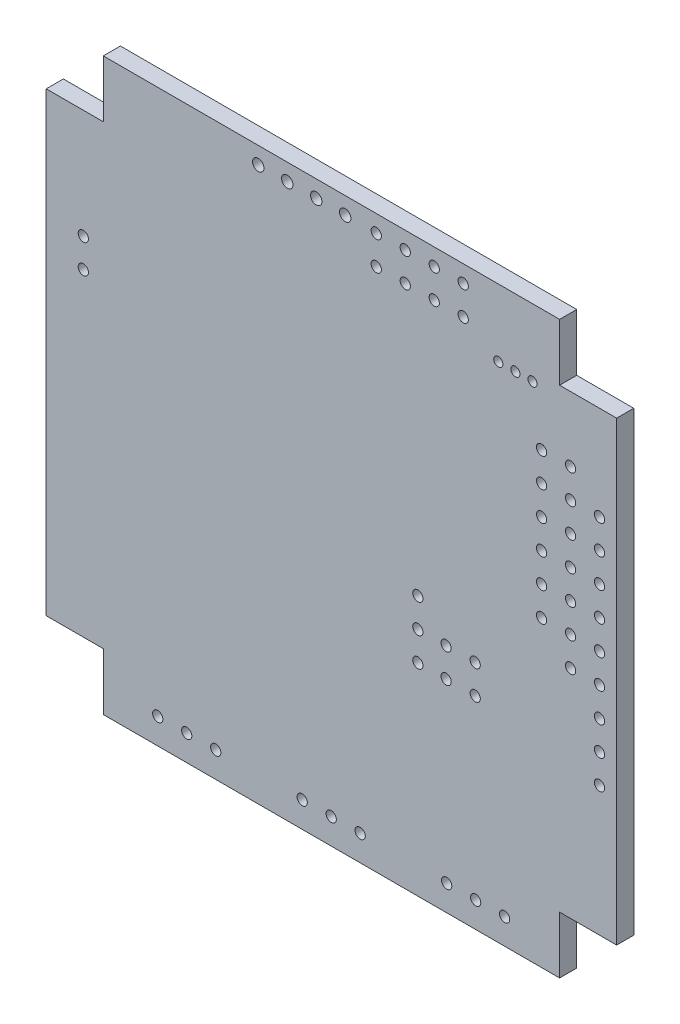
SolidWorks part; units mm, degrees
ref_plane "Спереди" through (0, 0, 0) normal (0, 0, 1) x (1, 0, 0)
ref_plane "Сверху" through (0, 0, 0) normal (0, 1, 0) x (1, 0, 0)
ref_plane "Справа" through (0, 0, 0) normal (1, 0, 0) x (0, 0, -1)
sketch "Эскиз3" plane through (0, 0, 0) normal (0, 0, 1) x (1, 0, 0)
  line L12 (24.0812, -17.7588) -> (24.0812, 22.2412)
  line L13 (19.0812, -17.7588) -> (24.0812, -17.7588)
  line L14 (19.0812, -22.7588) -> (19.0812, -17.7588)
  line L15 (-20.9188, -22.7588) -> (19.0812, -22.7588)
  line L16 (-20.9188, -17.7588) -> (-20.9188, -22.7588)
  line L17 (-25.9188, -17.7588) -> (-20.9188, -17.7588)
  line L18 (-25.9188, 22.2412) -> (-25.9188, -17.7588)
  line L19 (-20.9188, 22.2412) -> (-25.9188, 22.2412)
  line L20 (-20.9188, 27.2412) -> (-20.9188, 22.2412)
  line L21 (19.0812, 27.2412) -> (-20.9188, 27.2412)
  line L22 (19.0812, 22.2412) -> (19.0812, 27.2412)
  line L23 (24.0812, 22.2412) -> (19.0812, 22.2412)
  line L24 (24.0812, -17.7588) -> (24.0812, 22.2412)
  line L25 (19.0812, -17.7588) -> (24.0812, -17.7588)
  line L26 (19.0812, -22.7588) -> (19.0812, -17.7588)
  line L27 (-20.9188, -22.7588) -> (19.0812, -22.7588)
  line L28 (-20.9188, -17.7588) -> (-20.9188, -22.7588)
  line L29 (-25.9188, -17.7588) -> (-20.9188, -17.7588)
  line L30 (-25.9188, 22.2412) -> (-25.9188, -17.7588)
  line L31 (-20.9188, 22.2412) -> (-25.9188, 22.2412)
  line L32 (-20.9188, 27.2412) -> (-20.9188, 22.2412)
  line L33 (19.0812, 27.2412) -> (-20.9188, 27.2412)
  line L34 (19.0812, 22.2412) -> (19.0812, 27.2412)
  line L35 (24.0812, 22.2412) -> (19.0812, 22.2412)
  circle A1 centre (22.5813, 1.2412) radius 0.45
  circle A2 centre (22.5813, 1.2412) radius 0.45
  circle A3 centre (22.5813, 3.7912) radius 0.45
  circle A4 centre (22.5813, 3.7912) radius 0.45
  circle A5 centre (22.5813, 6.3412) radius 0.45
  circle A6 centre (22.5813, 6.3412) radius 0.45
  circle A7 centre (22.5813, 8.8912) radius 0.45
  circle A8 centre (22.5813, 8.8912) radius 0.45
  circle A9 centre (22.5813, 11.4412) radius 0.45
  circle A10 centre (22.5813, 11.4412) radius 0.45
  circle A11 centre (22.5813, 13.9912) radius 0.45
  circle A12 centre (22.5813, 13.9912) radius 0.45
  circle A13 centre (17.5013, 3.7912) radius 0.45
  circle A14 centre (17.5013, 3.7912) radius 0.45
  circle A15 centre (17.5013, 6.3412) radius 0.45
  circle A16 centre (17.5013, 6.3412) radius 0.45
  circle A17 centre (17.5013, 8.8912) radius 0.45
  circle A18 centre (17.5013, 8.8912) radius 0.45
  circle A19 centre (17.5013, 11.4412) radius 0.45
  circle A20 centre (17.5013, 11.4412) radius 0.45
  circle A21 centre (17.5013, 13.9912) radius 0.45
  circle A22 centre (17.5013, 13.9912) radius 0.45
  circle A23 centre (17.5013, 16.5412) radius 0.45
  circle A24 centre (17.5013, 16.5412) radius 0.45
  circle A25 centre (20.0413, 16.5412) radius 0.45
  circle A26 centre (20.0413, 16.5412) radius 0.45
  circle A27 centre (20.0413, 13.9912) radius 0.45
  circle A28 centre (20.0413, 13.9912) radius 0.45
  circle A29 centre (20.0413, 11.4412) radius 0.45
  circle A30 centre (20.0413, 11.4412) radius 0.45
  circle A31 centre (20.0413, 8.8912) radius 0.45
  circle A32 centre (20.0413, 8.8912) radius 0.45
  circle A33 centre (20.0413, 6.3412) radius 0.45
  circle A34 centre (20.0413, 6.3412) radius 0.45
  circle A35 centre (20.0413, 3.7912) radius 0.45
  circle A36 centre (20.0413, 3.7912) radius 0.45
  circle A37 centre (20.0413, 1.2412) radius 0.45
  circle A38 centre (20.0413, 1.2412) radius 0.45
  circle A39 centre (22.5812, -6.3888) radius 0.45
  circle A40 centre (22.5812, -6.3888) radius 0.45
  circle A41 centre (22.5812, -3.8488) radius 0.45
  circle A42 centre (22.5812, -3.8488) radius 0.45
  circle A43 centre (22.5812, -1.3088) radius 0.45
  circle A44 centre (22.5812, -1.3088) radius 0.45
  circle A45 centre (3.0112, 25.7412) radius 0.45
  circle A46 centre (3.0112, 25.7412) radius 0.45
  circle A47 centre (5.5512, 23.2012) radius 0.45
  circle A48 centre (5.5512, 23.2012) radius 0.45
  circle A49 centre (5.5512, 25.7412) radius 0.45
  circle A50 centre (5.5512, 25.7412) radius 0.45
  circle A51 centre (8.0912, 23.2012) radius 0.45
  circle A52 centre (8.0912, 23.2012) radius 0.45
  circle A53 centre (8.0912, 25.7412) radius 0.45
  circle A54 centre (8.0912, 25.7412) radius 0.45
  circle A55 centre (10.6312, 25.7412) radius 0.45
  circle A56 centre (10.6312, 25.7412) radius 0.45
  circle A57 centre (10.6312, 23.2012) radius 0.45
  circle A58 centre (10.6312, 23.2012) radius 0.45
  circle A59 centre (13.7062, 21.3412) radius 0.4
  circle A60 centre (13.7062, 21.3412) radius 0.4
  circle A61 centre (15.2062, 21.3412) radius 0.4
  circle A62 centre (15.2062, 21.3412) radius 0.4
  circle A63 centre (16.7062, 21.3412) radius 0.4
  circle A64 centre (16.7062, 21.3412) radius 0.4
  circle A65 centre (6.6563, 0.0412) radius 0.45
  circle A66 centre (6.6563, 0.0412) radius 0.45
  circle A67 centre (6.6563, -5.0388) radius 0.45
  circle A68 centre (6.6563, -5.0388) radius 0.45
  circle A69 centre (6.6563, -2.4988) radius 0.45
  circle A70 centre (6.6563, -2.4988) radius 0.45
  circle A71 centre (9.1313, -2.4988) radius 0.45
  circle A72 centre (9.1313, -2.4988) radius 0.45
  circle A73 centre (9.1313, -5.0388) radius 0.45
  circle A74 centre (9.1313, -5.0388) radius 0.45
  circle A75 centre (11.6814, -2.4988) radius 0.45
  circle A76 centre (11.6814, -2.4988) radius 0.45
  circle A77 centre (14.2613, -20.5088) radius 0.45
  circle A78 centre (14.2613, -20.5088) radius 0.45
  circle A79 centre (11.7213, -20.5088) radius 0.45
  circle A80 centre (11.7213, -20.5088) radius 0.45
  circle A81 centre (9.1813, -20.5088) radius 0.45
  circle A82 centre (9.1813, -20.5088) radius 0.45
  circle A83 centre (1.5988, -20.5088) radius 0.45
  circle A84 centre (1.5988, -20.5088) radius 0.45
  circle A85 centre (-0.9412, -20.5088) radius 0.45
  circle A86 centre (-0.9412, -20.5088) radius 0.45
  circle A87 centre (-3.4812, -20.5088) radius 0.45
  circle A88 centre (-3.4812, -20.5088) radius 0.45
  circle A89 centre (-11.0637, -20.5088) radius 0.45
  circle A90 centre (-11.0637, -20.5088) radius 0.45
  circle A91 centre (-13.6037, -20.5088) radius 0.45
  circle A92 centre (-13.6037, -20.5088) radius 0.45
  circle A93 centre (-16.1437, -20.5088) radius 0.45
  circle A94 centre (-16.1437, -20.5088) radius 0.45
  circle A95 centre (-22.6688, 10.1412) radius 0.45
  circle A96 centre (-22.6688, 10.1412) radius 0.45
  circle A97 centre (-22.6688, 12.6812) radius 0.45
  circle A98 centre (-22.6688, 12.6812) radius 0.45
  circle A99 centre (-7.3338, 25.7562) radius 0.5
  circle A100 centre (-7.3338, 25.7562) radius 0.5
  circle A101 centre (-4.7938, 25.7562) radius 0.5
  circle A102 centre (-4.7938, 25.7562) radius 0.5
  circle A103 centre (-2.2538, 25.7562) radius 0.5
  circle A104 centre (-2.2538, 25.7562) radius 0.5
  circle A105 centre (0.2862, 25.7562) radius 0.5
  circle A106 centre (0.2862, 25.7562) radius 0.5
  circle A107 centre (3.0112, 23.2012) radius 0.45
  circle A108 centre (3.0112, 23.2012) radius 0.45
  circle A109 centre (11.6814, -5.0388) radius 0.45
  circle A110 centre (11.6814, -5.0388) radius 0.45
  dimension "D1" = 0
  dimension "D2" = 0
  dimension "D3" = 0
  dimension "D4" = 0
  dimension "D5" = 0
  dimension "D6" = 0
  dimension "D7" = 0
  dimension "D8" = 0
  dimension "D9" = 0
  dimension "D10" = 0
  dimension "D11" = 0
  dimension "D12" = 0
  dimension "D13" = 0
  dimension "D14" = 0
  dimension "D15" = 0
  dimension "D16" = 0
  dimension "D17" = 0
  dimension "D18" = 0
  dimension "D19" = 0
  dimension "D20" = 0
  dimension "D21" = 0
  dimension "D22" = 0
  dimension "D23" = 0
  dimension "D24" = 0
  dimension "D25" = 0
  dimension "D26" = 0
  dimension "D27" = 0
  dimension "D28" = 0
  dimension "D29" = 0
  dimension "D30" = 0
  dimension "D31" = 0
  dimension "D32" = 0
  dimension "D33" = 0
  dimension "D34" = 0
  dimension "D35" = 0
  dimension "D36" = 0
  dimension "D37" = 0
  dimension "D38" = 0
  dimension "D39" = 0
  dimension "D40" = 0
  dimension "D41" = 0
  dimension "D42" = 0
  dimension "D43" = 0
  dimension "D44" = 0
  dimension "D45" = 0
  dimension "D46" = 0
  dimension "D47" = 0
  dimension "D48" = 0
  dimension "D49" = 0
  dimension "D50" = 0
  dimension "D51" = 0
  dimension "D52" = 0
  dimension "D53" = 0
  dimension "D54" = 0
  dimension "D55" = 0
  dimension "D56" = 0
extrude "Бобышка-Вытянуть1" add sketch "Эскиз3" along normal blind 1.5
